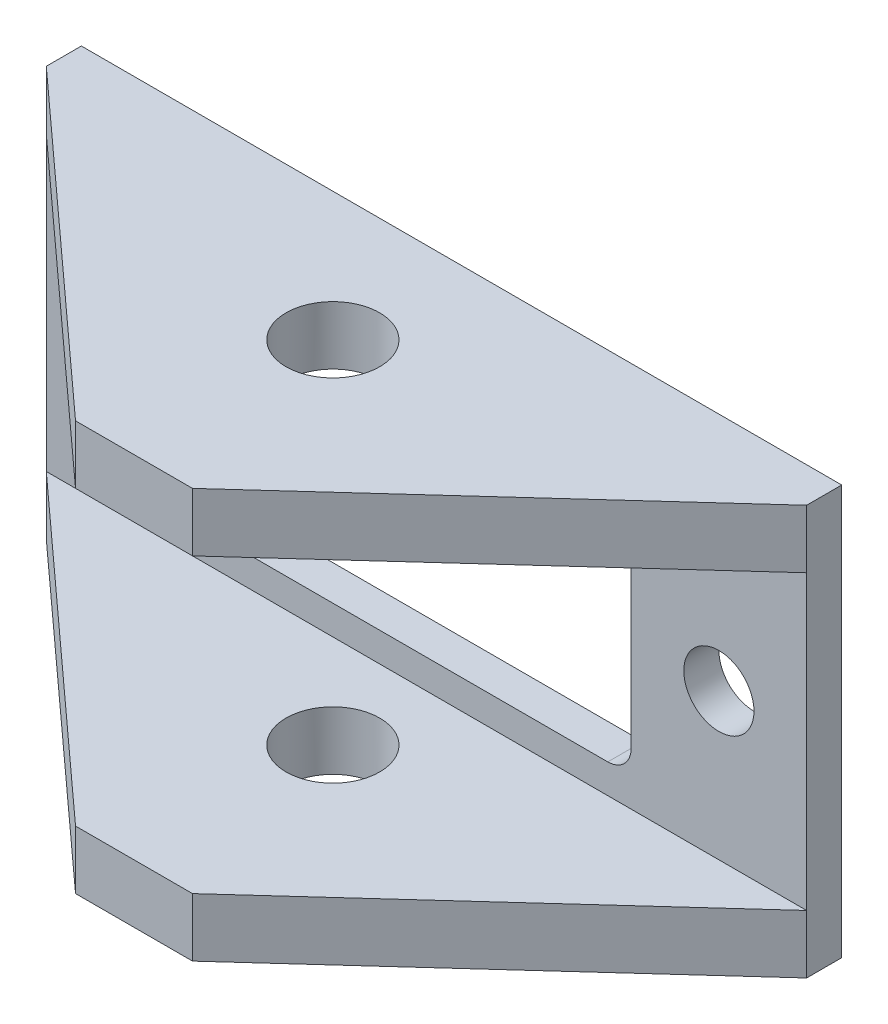
SolidWorks part; units mm, degrees
material "7075-T6 (SN)"
ref_plane "Front Plane" through (0, 0, 0) normal (0, 0, 1) x (1, 0, 0)
ref_plane "Top Plane" through (0, 0, 0) normal (0, 1, 0) x (1, 0, 0)
ref_plane "Right Plane" through (0, 0, 0) normal (1, 0, 0) x (0, 0, -1)
sketch "Sketch1" plane through (0, 0, 0) normal (0, 1, 0) x (1, 0, 0)
  line L0 (0, 0) -> (0, -15.5)
  line L1 (-32.5, 12.5) -> (32.5, 12.5)
  line L5 (-32.5, 12.5) -> (0, 0) construction
  line L6 (0, 0) -> (32.5, 12.5) construction
  line L7 (-5, -15.5) -> (5, -15.5)
  line L8 (-32.5, 12.5) -> (-32.5, 9.5)
  line L9 (32.5, 12.5) -> (32.5, 9.5)
  line L10 (-32.5, 9.5) -> (-5, -15.5)
  line L11 (5, -15.5) -> (32.5, 9.5)
  point P0 (0, 0)
  point P10 (0, -15.5)
  dimension "D1" = 28
  dimension "D2" = 65
  dimension "D3" = 10
extrude "Boss-Extrude1" add sketch "Sketch1" along normal blind 35
sketch "Sketch4" plane through (0, 0, 0) normal (0, 0, 1) x (1, 0, 0)
  line L0 (32.5, 0) -> (-32.5, 35)
  line L1 (32.5, 35) -> (32.5, 0) construction
  line L2 (-32.5, 30) -> (32.5, 30)
  line L3 (-32.5, 30) -> (-32.5, 5)
  line L4 (-32.5, 5) -> (32.5, 5)
  line L5 (32.5, 30) -> (32.5, 5)
  line L6 (-32.5, 30) -> (32.5, 5) construction
  line L7 (-32.5, 5) -> (32.5, 30) construction
  point P4 (0, 17.5)
  dimension "D1" = 25
extrude "Cut-Extrude1" cut sketch "Sketch4" against normal up to vertex (9.5 mm away) and the other way up to surface (15.5 mm away) contours L5 L2 L0 L4 | L3 L4 L0 L2 other way up to face at (0, 17.5, 15.5)
sketch "Sketch5" plane through (0, 0, 0) normal (0, 0, 1) x (1, 0, 0)
  line L0 (-32.5, 30) -> (32.5, 5)
  line L1 (-25, 17.5) -> (25, 17.5)
  line L2 (-17.5, 27.5) -> (17.5, 27.5)
  line L3 (-17.5, 27.5) -> (-17.5, 7.5)
  line L4 (-17.5, 7.5) -> (17.5, 7.5)
  line L5 (17.5, 27.5) -> (17.5, 7.5)
  line L6 (-17.5, 27.5) -> (17.5, 7.5) construction
  line L7 (-17.5, 7.5) -> (17.5, 27.5) construction
  circle A0 centre (-25, 17.5) radius 3
  circle A1 centre (25, 17.5) radius 3
  point P4 (0, 17.5)
  point P12 (0, 17.5)
  dimension "D1" = 20
  dimension "D2" = 35
extrude "Cut-Extrude2" cut sketch "Sketch5" against normal through all both and the other way through all
ref_plane "Plane2" through (0, 35, 0) normal (0, 1, 0) x (1, 0, 0)
sketch "Sketch6" plane through (0, 35, 0) normal (0, 1, 0) x (1, 0, 0)
  line L0 (0, 12.5) -> (0, 1.5)
  line L1 (-32.5, 12.5) -> (32.5, 12.5) construction
  circle A3 centre (0, 1.5) radius 4
fillet "Fillet1" radius 2 4 edges at (17.5, 27.5, -11) (-17.5, 27.5, -11) (-17.5, 7.5, -11) (17.5, 7.5, -11)
extrude "Cut-Extrude3" cut sketch "Sketch6" against normal through all both and the other way through all
